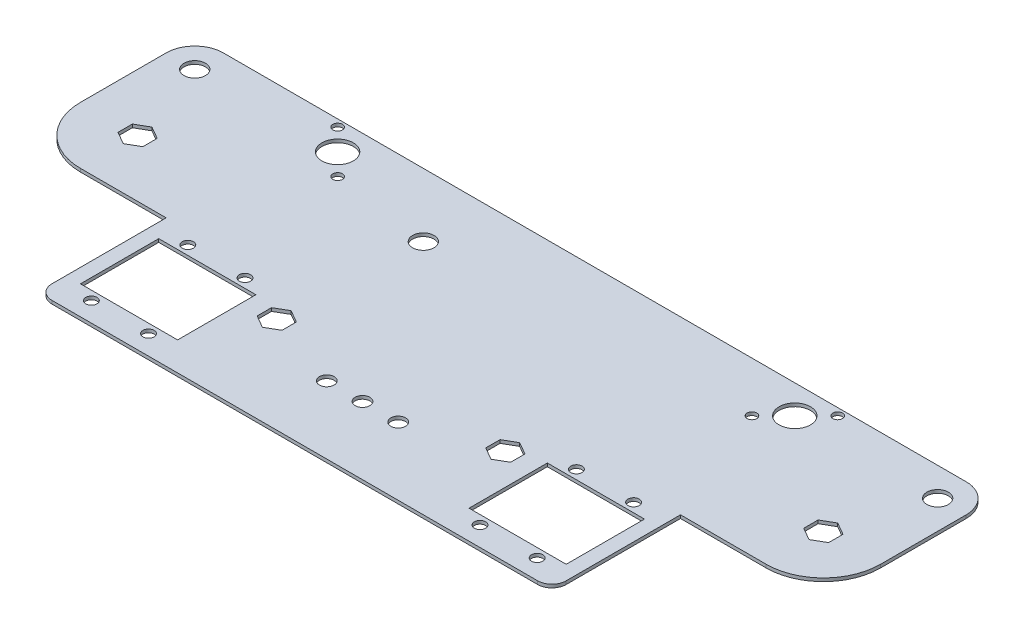
SolidWorks part; units mm, degrees
ref_plane "Front Plane" through (0, 0, 0) normal (0, 0, 1) x (1, 0, 0)
ref_plane "Top Plane" through (0, 0, 0) normal (0, 1, 0) x (1, 0, 0)
ref_plane "Right Plane" through (0, 0, 0) normal (1, 0, 0) x (0, 0, -1)
sketch "Sketch1" plane through (0, 0, 0) normal (0, 1, 0) x (1, 0, 0)
  line L0 (-30.1085, -296.4752) -> (-30.1085, -331.2732) construction
  line L1 (-58.0485, -286.8232) -> (-96.1485, -286.8232)
  line L2 (-58.0485, -286.8232) -> (-58.0485, -337.6232)
  line L3 (-51.6985, -343.9732) -> (164.2015, -343.9732)
  line L5 (-121.5485, -261.4232) -> (-121.5485, -223.3232)
  line L6 (-108.8485, -210.6232) -> (221.3515, -210.6232)
  line L7 (234.0515, -223.3232) -> (234.0515, -261.4232)
  line L8 (208.6515, -286.8232) -> (170.5515, -286.8232)
  line L9 (-51.6985, -296.4752) -> (-8.5185, -296.4752)
  line L10 (-51.6985, -296.4752) -> (-51.6985, -331.2732)
  line L11 (-51.6985, -331.2732) -> (-8.5185, -331.2732)
  line L12 (-8.5185, -296.4752) -> (-8.5185, -331.2732)
  line L13 (121.0215, -296.4752) -> (164.2015, -296.4752)
  line L14 (164.2015, -296.4752) -> (164.2015, -331.2732)
  line L15 (121.0215, -331.2732) -> (164.2015, -331.2732)
  line L16 (142.6115, -296.4752) -> (142.6115, -331.2732) construction
  line L17 (-51.6985, -313.8742) -> (-8.5185, -313.8742) construction
  line L18 (121.0215, -313.8742) -> (164.2015, -313.8742) construction
  line L19 (121.0215, -296.4752) -> (121.0215, -331.2732)
  line L20 (56.2515, -343.9732) -> (56.2515, 211.8848) construction
  line L21 (10.976, -304.3638) -> (10.976, -297.9846)
  line L22 (10.976, -297.9846) -> (5.4515, -294.7951)
  line L23 (5.4515, -294.7951) -> (-0.073, -297.9846)
  line L24 (-0.073, -297.9846) -> (-0.073, -304.3638)
  line L25 (-0.073, -304.3638) -> (5.4515, -307.5533)
  line L26 (5.4515, -307.5533) -> (10.976, -304.3638)
  line L27 (170.5515, -286.8232) -> (170.5515, -337.6232)
  line L28 (107.0515, -307.5533) -> (101.527, -304.3638)
  line L29 (112.576, -304.3638) -> (107.0515, -307.5533)
  line L30 (112.576, -297.9846) -> (112.576, -304.3638)
  line L31 (107.0515, -294.7951) -> (112.576, -297.9846)
  line L32 (101.527, -297.9846) -> (107.0515, -294.7951)
  line L33 (101.527, -304.3638) -> (101.527, -297.9846)
  line L34 (-19.9485, -210.6232) -> (-19.9485, -242.8626) construction
  line L35 (-90.624, -258.2336) -> (-96.1485, -255.0441)
  line L36 (-96.1485, -255.0441) -> (-101.673, -258.2336)
  line L37 (-101.673, -258.2336) -> (-101.673, -264.6128)
  line L38 (-101.673, -264.6128) -> (-96.1485, -267.8023)
  line L39 (-96.1485, -267.8023) -> (-90.624, -264.6128)
  line L40 (-90.624, -264.6128) -> (-90.624, -258.2336)
  line L41 (214.176, -264.6128) -> (208.6515, -267.8023)
  line L42 (214.176, -258.2336) -> (214.176, -264.6128)
  line L43 (208.6515, -255.0441) -> (214.176, -258.2336)
  line L44 (203.127, -258.2336) -> (208.6515, -255.0441)
  line L45 (208.6515, -267.8023) -> (203.127, -264.6128)
  line L46 (203.127, -264.6128) -> (203.127, -258.2336)
  circle A0 centre (-42.8085, -292.443) radius 2.5
  circle A1 centre (-17.4085, -292.443) radius 2.5
  circle A2 centre (-17.4085, -335.3055) radius 2.5
  circle A3 centre (-42.8085, -335.3055) radius 2.5
  circle A4 centre (129.9115, -292.443) radius 2.5
  circle A5 centre (155.3115, -292.443) radius 2.5
  circle A6 centre (155.3115, -335.3055) radius 2.5
  circle A7 centre (129.9115, -335.3055) radius 2.5
  circle A8 centre (5.4515, -301.1742) radius 5.5245 construction
  circle A9 centre (107.0515, -301.1742) radius 5.5245 construction
  arc A10 (-96.1485, -286.8232) -> (-121.5485, -261.4232) centre (-96.1485, -261.4232) cw
  arc A11 (234.0515, -261.4232) -> (208.6515, -286.8232) centre (208.6515, -261.4232) cw
  circle A12 centre (40.3765, -313.8742) radius 3.2639
  circle A13 centre (56.2515, -313.8742) radius 3.2639
  circle A14 centre (72.1265, -313.8742) radius 3.2639
  circle A15 centre (-96.1485, -261.4232) radius 5.5245 construction
  circle A16 centre (-45.3485, -223.3232) radius 6.985
  circle A17 centre (-54.8735, -213.7982) radius 2.159
  circle A18 centre (-35.8235, -232.8482) radius 2.159
  circle A19 centre (8.2455, -238.8172) radius 4.7625
  circle A20 centre (148.3265, -232.8482) radius 2.159
  circle A21 centre (157.8515, -223.3232) radius 6.985
  circle A22 centre (167.3765, -213.7982) radius 2.159
  circle A23 centre (208.6515, -261.4232) radius 5.5245 construction
  arc A24 (221.3515, -210.6232) -> (234.0515, -223.3232) centre (221.3515, -223.3232) cw
  arc A25 (-121.5485, -223.3232) -> (-108.8485, -210.6232) centre (-108.8485, -223.3232) cw
  arc A26 (164.2015, -343.9732) -> (170.5515, -337.6232) centre (164.2015, -337.6232) ccw
  arc A27 (-58.0485, -337.6232) -> (-51.6985, -343.9732) centre (-51.6985, -337.6232) ccw
  circle A28 centre (-108.8485, -223.3232) radius 4.7625
  circle A30 centre (221.3515, -223.3232) radius 4.7625
  point P61 (-121.5485, -286.8232)
  point P105 (-121.5485, -210.6232)
  point P110 (-58.0485, -343.9732)
  dimension "D11" = 5
  dimension "D12" = 42.8625
  dimension "D13" = 25.4
  dimension "D17" = 63.5
  dimension "D18" = 25.4
  dimension "D14" = 25.4
  dimension "D15" = 12.7
  dimension "D19" = 6.5278
  dimension "D21" = 6.5278
  dimension "D22" = 6.5278
  dimension "D23" = 15.875
  dimension "D24" = 15.875
  dimension "D25" = 12.7
  dimension "D28" = 13.97
  dimension "D30" = 4.318
  dimension "D31" = 4.318
  dimension "D32" = 9.525
  dimension "D33" = 9.525
  dimension "D34" = 9.525
  dimension "D35" = 9.525
  dimension "D36" = 25.4
  dimension "D38" = 9.525
  dimension "D40" = 6.35
  dimension "D41" = 9.525
  dimension "D42" = 9.525
  dimension "D2" = 57.15
  dimension "D3" = 43.18
  dimension "D4" = 34.798
  dimension "D5" = 12.7
  dimension "D6" = 6.35
  dimension "D7" = 2
  dimension "D8" = 11.049
  dimension "D9" = 12.7
  dimension "D10" = 101.6
  dimension "D16" = 25.4
  dimension "D20" = 76.2
  dimension "D26" = 11.049
  dimension "D27" = 12.7
  dimension "D29" = 101.6
  dimension "D37" = 28.194
  dimension "D39" = 28.194
extrude "Boss-Extrude1" add sketch "Sketch1" along normal blind 1.4478
